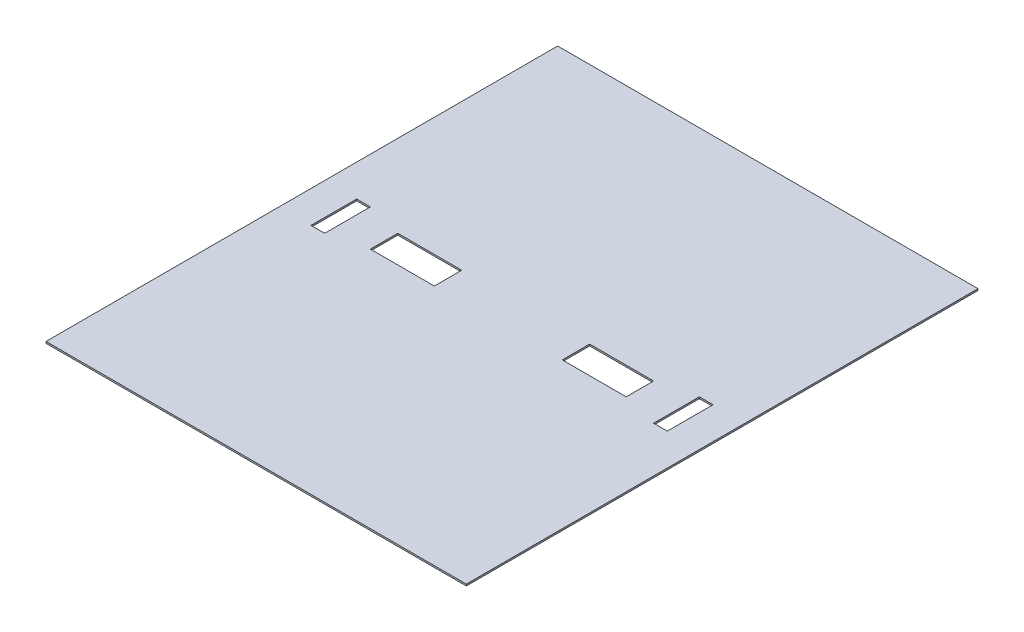
SolidWorks part; units mm, degrees
material "Plain Carbon Steel"
ref_plane "Front Plane" through (0, 0, 0) normal (0, 0, 1) x (1, 0, 0)
ref_plane "Top Plane" through (0, 0, 0) normal (0, 1, 0) x (1, 0, 0)
ref_plane "Right Plane" through (0, 0, 0) normal (1, 0, 0) x (0, 0, -1)
ref_plane "Plane1" through (0, -25.4, 330.2) normal (0, 1, 0) x (1, 0, 0)
sketch "Sketch1" plane through (0, -25.4, 330.2) normal (0, 1, 0) x (1, 0, 0)
  line L1 (292.1, 685.8) -> (-292.1, 685.8)
  line L2 (292.1, 685.8) -> (292.1, -25.4)
  line L3 (292.1, -25.4) -> (-292.1, -25.4)
  line L4 (-292.1, 685.8) -> (-292.1, -25.4)
  line L5 (292.1, 685.8) -> (-292.1, -25.4) construction
  line L6 (292.1, -25.4) -> (-292.1, 685.8) construction
  point P0 (0, 330.2)
extrude "Boss-Extrude1" add sketch "Sketch1" against normal blind 2.286
sketch "Sketch3" plane through (0, -27.686, 0) normal (0, -1, 0) x (-1, 0, 0)
  line L0 (228.6, 0) -> (177.8, 0) construction
  line L1 (247.65, -31.75) -> (228.6, -31.75)
  line L2 (247.65, -31.75) -> (247.65, 31.75)
  line L3 (247.65, 31.75) -> (228.6, 31.75)
  line L4 (228.6, -31.75) -> (228.6, 31.75)
  line L5 (292.1, 355.6) -> (292.1, -355.6) construction
  line L6 (177.8, -19.05) -> (88.9, -19.05)
  line L7 (177.8, -19.05) -> (177.8, 19.05)
  line L8 (177.8, 19.05) -> (88.9, 19.05)
  line L9 (88.9, -19.05) -> (88.9, 19.05)
  dimension "D1" = 38.1
  dimension "D2" = 63.5
  dimension "D3" = 19.05
  dimension "D4" = 88.9
  dimension "D5" = 44.45
  dimension "D6" = 50.8
extrude "Cut-Extrude1" cut sketch "Sketch3" against normal through all
mirror "Mirror1" about plane through (0, 0, 0) normal (1, 0, 0) of "Cut-Extrude1"
